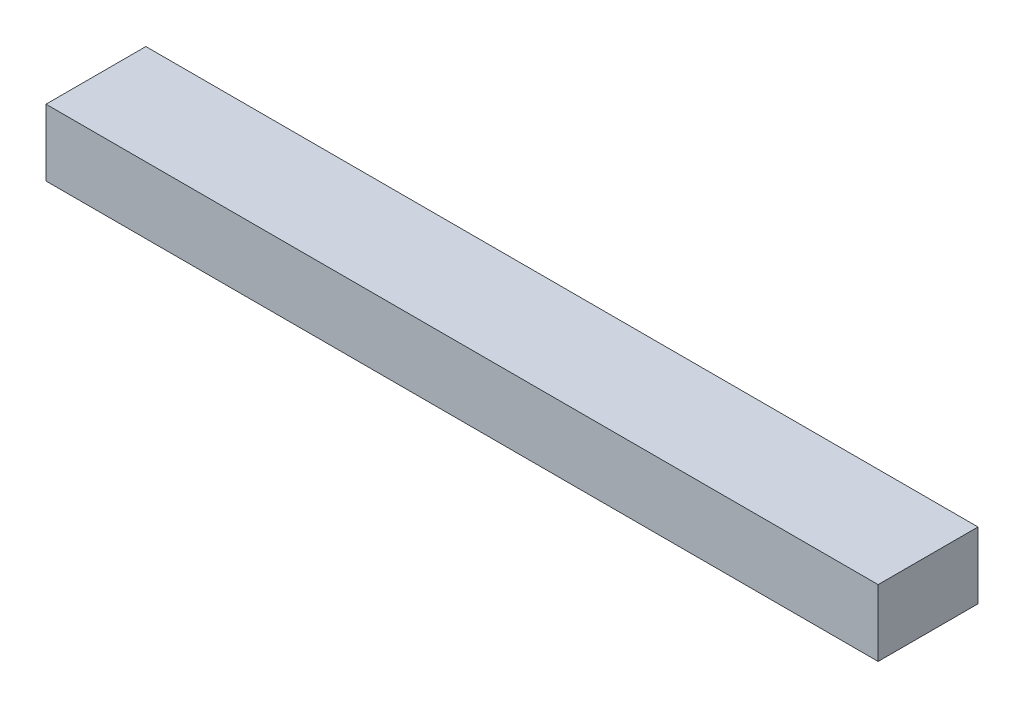
SolidWorks part; units mm, degrees
ref_plane "Front Plane" through (0, 0, 0) normal (0, 0, 1) x (1, 0, 0)
ref_plane "Top Plane" through (0, 0, 0) normal (0, 1, 0) x (1, 0, 0)
ref_plane "Right Plane" through (0, 0, 0) normal (1, 0, 0) x (0, 0, -1)
sketch "Sketch1" plane through (0, 0, 0) normal (0, 1, 0) x (1, 0, 0)
  line L1 (-50, -6) -> (50, -6)
  line L2 (-50, -6) -> (-50, 6)
  line L3 (-50, 6) -> (50, 6)
  line L4 (50, -6) -> (50, 6)
  line L5 (-50, -6) -> (50, 6) construction
  line L6 (-50, 6) -> (50, -6) construction
  point P0 (0, 0)
  dimension "D1" = 12
  dimension "D2" = 100
extrude "Boss-Extrude1" add sketch "Sketch1" along normal blind 8
